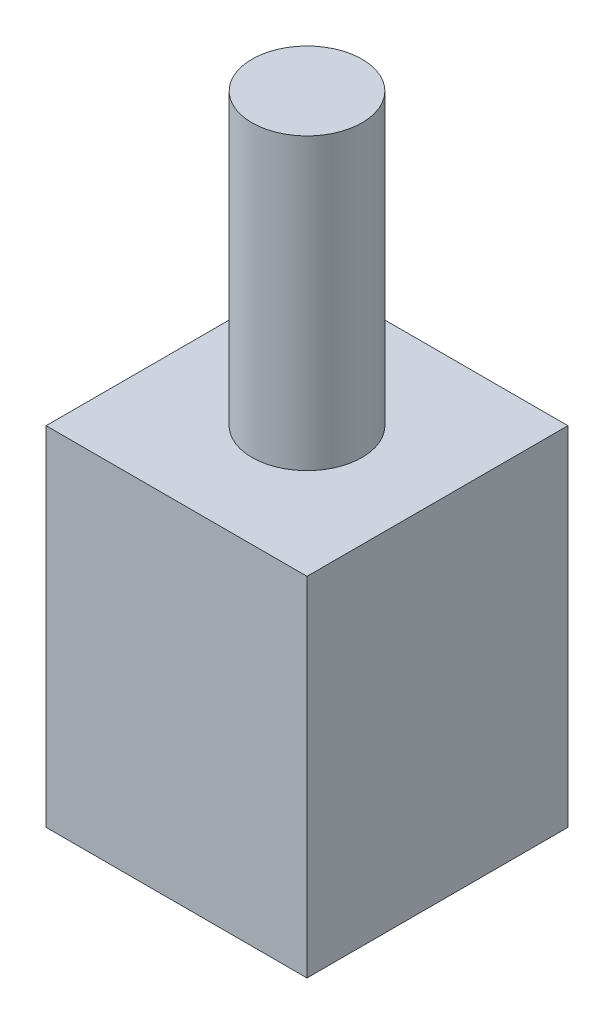
SolidWorks part; units mm, degrees
ref_plane "前视基准面" through (0, 0, 0) normal (0, 0, 1) x (1, 0, 0)
ref_plane "上视基准面" through (0, 0, 0) normal (0, 1, 0) x (1, 0, 0)
ref_plane "右视基准面" through (0, 0, 0) normal (1, 0, 0) x (0, 0, -1)
other "Configuration Table"
sketch "草图1" plane through (0, 0, 0) normal (0, 1, 0) x (1, 0, 0)
  line L1 (-3.8219, 4.1301) -> (5.1781, 4.1301)
  line L2 (-3.8219, 4.1301) -> (-3.8219, -4.8699)
  line L3 (-3.8219, -4.8699) -> (5.1781, -4.8699)
  line L4 (5.1781, 4.1301) -> (5.1781, -4.8699)
  dimension "D1" = 9
  dimension "D2" = 9
extrude "凸台-拉伸1" add sketch "草图1" along normal blind 12
sketch "草图2" plane through (0, 12, 0) normal (0, 1, 0) x (1, 0, 0)
  line L0 (-3.8219, 4.1301) -> (-3.8219, -4.8699) construction
  line L1 (5.1781, 4.1301) -> (-3.8219, 4.1301) construction
  circle A0 centre (0.6781, -0.3699) radius 1.9
  dimension "D1" = 4.5
  dimension "D2" = 4.5
extrude "凸台-拉伸2" add sketch "草图2" along normal blind 10
